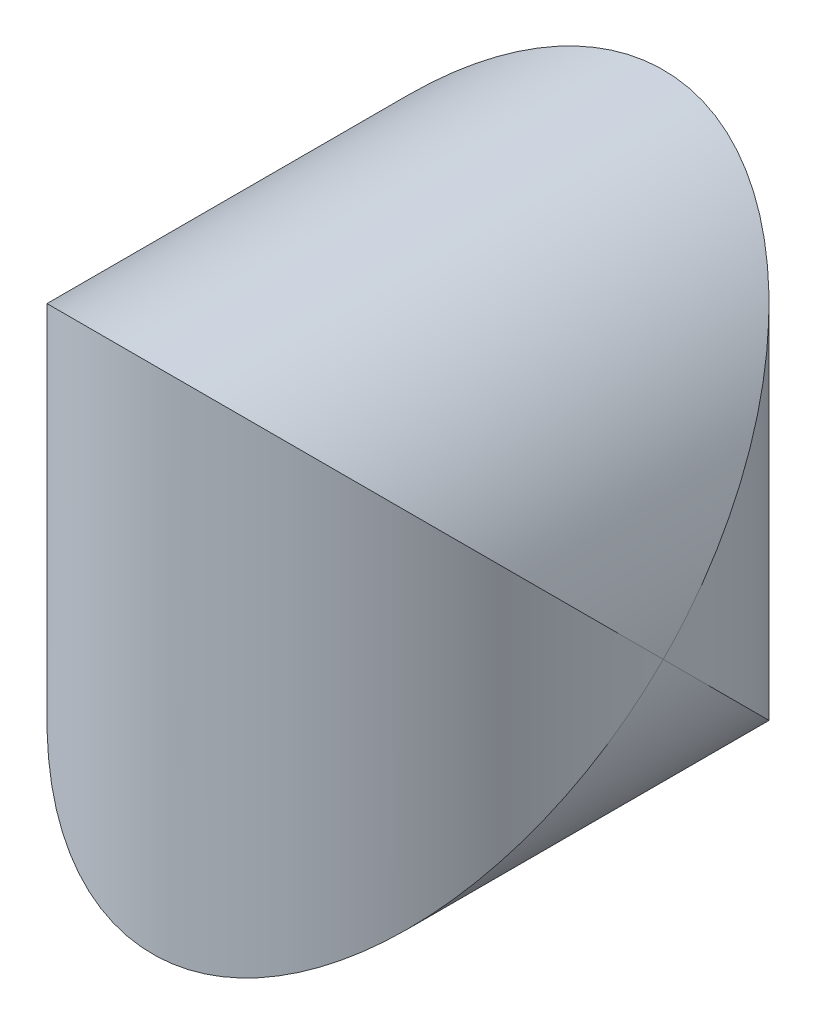
SolidWorks part; units mm, degrees
ref_plane "前视基准面" through (0, 0, 0) normal (0, 0, 1) x (1, 0, 0)
ref_plane "上视基准面" through (0, 0, 0) normal (0, 1, 0) x (1, 0, 0)
ref_plane "右视基准面" through (0, 0, 0) normal (1, 0, 0) x (0, 0, -1)
other "Configuration Table"
sketch "草图1" plane through (0, 0, 0) normal (0, 0, 1) x (1, 0, 0)
  circle A0 centre (0, 0) radius 15
  dimension "D1" = 30
extrude "凸台-拉伸1" add sketch "草图1" along normal mid plane 30
sketch "草图2" plane through (0, 0, 0) normal (0, 1, 0) x (1, 0, 0)
  circle A0 centre (0, 0) radius 15
  dimension "D1" = 30
extrude "切除-拉伸1" cut sketch "草图2" against normal mid plane 30 flip side to cut
